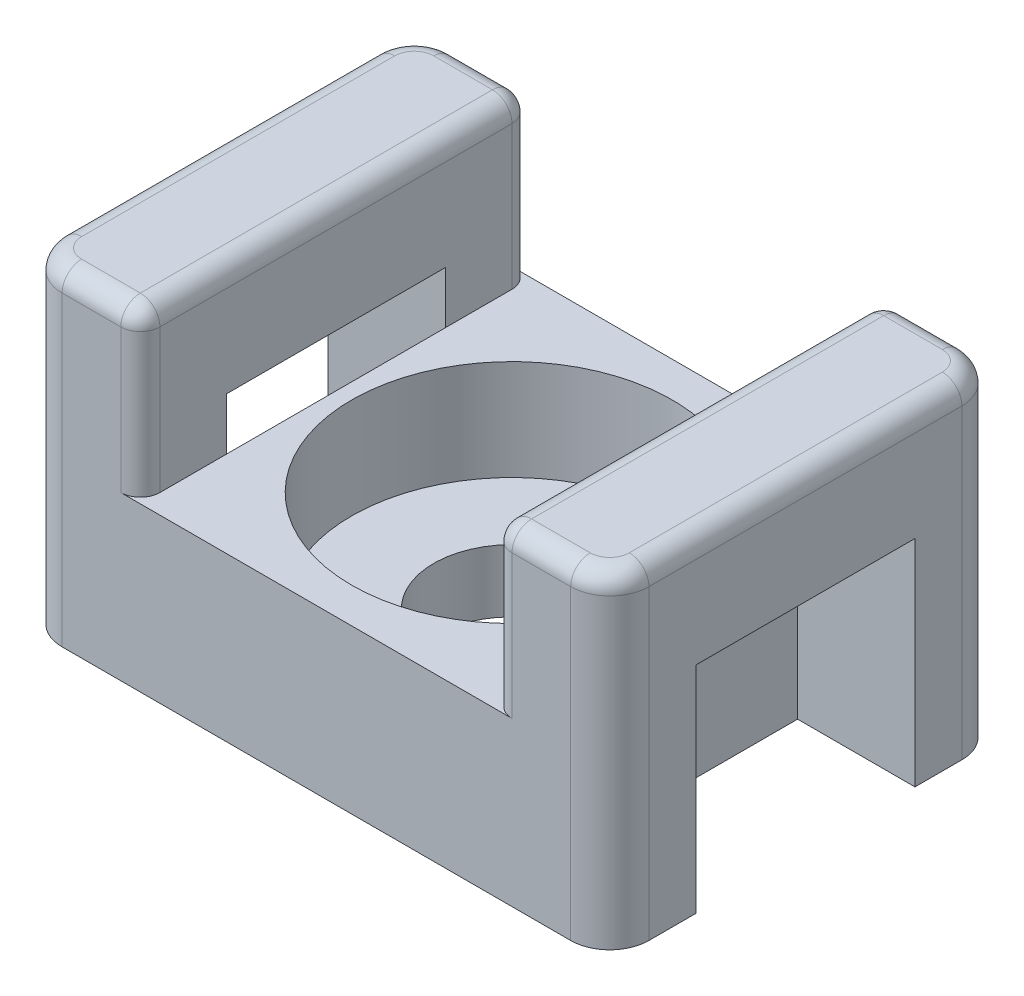
SolidWorks part; units mm, degrees
ref_plane "Front Plane" through (0, 0, 0) normal (0, 0, 1) x (1, 0, 0)
ref_plane "Top Plane" through (0, 0, 0) normal (0, 1, 0) x (1, 0, 0)
ref_plane "Right Plane" through (0, 0, 0) normal (1, 0, 0) x (0, 0, -1)
sketch "Sketch1" plane through (0, 0, 0) normal (0, 1, 0) x (1, 0, 0)
  line L1 (7.1438, -4.7625) -> (-7.1437, -4.7625)
  line L2 (7.1438, -4.7625) -> (7.1438, 4.7625)
  line L3 (7.1438, 4.7625) -> (-7.1437, 4.7625)
  line L4 (-7.1437, -4.7625) -> (-7.1437, 4.7625)
  line L5 (7.1438, -4.7625) -> (-7.1437, 4.7625) construction
  line L6 (7.1438, 4.7625) -> (-7.1437, -4.7625) construction
  circle A0 centre (0, 0) radius 1.905
  dimension "MT" = 3.81
  dimension "Length" = 14.2875
  dimension "Width" = 9.525
extrude "Boss-Extrude1" add sketch "Sketch1" along normal blind 7.9375
sketch "Sketch2" plane through (0, 0, 4.7625) normal (0, 0, 1) x (1, 0, 0)
  line L0 (-4.2862, 7.9375) -> (-4.2862, 3.9688)
  line L1 (-7.1437, 7.9375) -> (7.1438, 7.9375) construction
  line L2 (-4.2862, 3.9688) -> (4.2862, 3.9688)
  line L3 (4.2862, 3.9688) -> (4.2862, 7.9375)
  line L4 (0, 0) -> (0, 3.9688) construction
  line L5 (-7.1437, 0) -> (7.1438, 0) construction
  line L6 (4.2862, 3.9688) -> (7.1437, 3.9688) construction
  line L7 (7.1438, 7.9375) -> (7.1438, 0) construction
  line L8 (-4.2862, 7.9375) -> (4.2862, 7.9375)
  line L9 (-7.1437, 7.9375) -> (-7.1437, 0) construction
  dimension "D1" = 8.5725
  dimension "D2" = 2.8575
extrude "Cut-Extrude1" cut sketch "Sketch2" against normal through all
sketch "Sketch3" plane through (0, 0, 0) normal (1, 0, 0) x (0, 0, -1)
  line L0 (0, 0) -> (0, 3.9688) construction
  line L1 (-2.667, 5.2388) -> (2.667, 5.2388)
  line L2 (-2.667, 5.2388) -> (-2.667, 3.9688)
  line L3 (-2.667, 3.9688) -> (2.667, 3.9688)
  line L4 (2.667, 5.2388) -> (2.667, 3.9688)
  line L5 (-4.7625, 0) -> (4.7625, 0) construction
  line L6 (4.7625, 3.9688) -> (-4.7625, 3.9688) construction
  dimension "CH" = 1.27
  dimension "CW" = 5.334
extrude "Cut-Extrude2" cut sketch "Sketch3" against normal through all both and the other way through all
sketch "Sketch4" plane through (7.1438, 0, 0) normal (1, 0, 0) x (0, 0, -1)
  line L0 (-4.7625, 0) -> (4.7625, 0) construction
  line L1 (-2.667, 3.9688) -> (2.667, 3.9688)
  line L2 (-2.667, 3.9688) -> (-2.667, 0)
  line L3 (-2.667, 0) -> (2.667, 0)
  line L4 (2.667, 3.9688) -> (2.667, 0)
  line L5 (2.667, 3.9688) -> (2.667, 5.2388) construction
extrude "Cut-Extrude3" cut sketch "Sketch4" against normal up to vertex
sketch "Sketch5" plane through (-7.1437, 0, 0) normal (-1, 0, 0) x (0, 0, 1)
  line L4 (2.667, 3.9688) -> (-2.667, 3.9688)
  line L5 (-2.667, 3.9688) -> (-2.667, 0)
  line L6 (-2.667, 0) -> (2.667, 0)
  line L7 (2.667, 0) -> (2.667, 3.9688)
  line L8 (2.667, 3.9688) -> (-2.667, 3.9688)
  line L9 (-2.667, 3.9688) -> (-2.667, 0)
  line L10 (-2.667, 0) -> (2.667, 0)
  line L11 (2.667, 0) -> (2.667, 3.9688)
  dimension "D1" = 0
extrude "Cut-Extrude4" cut sketch "Sketch5" against normal up to vertex
sketch "Sketch6" plane through (0, 3.9688, 0) normal (0, 1, 0) x (1, 0, 0)
  line L10 (3.9053, 2.667) -> (3.9053, -2.667)
  line L11 (3.9053, 2.667) -> (3.9053, -2.667) construction
  circle A0 centre (0, 0) radius 3.9053
  dimension "D1" = 0.381
extrude "Cut-Extrude5" cut sketch "Sketch6" against normal offset from surface (2.4448 mm away) 1.524
fillet "Fillet2" radius 0.9525
fillet "Fillet3" radius 0.4762
equation "\"D1@Sketch2\"=\"Length@Sketch1\"*.6"
equation "\"D1@Fillet2\"=\"D2@Sketch2\"/3"
equation "\"D1@Fillet3\"=\"D1@Fillet2\"/2"
